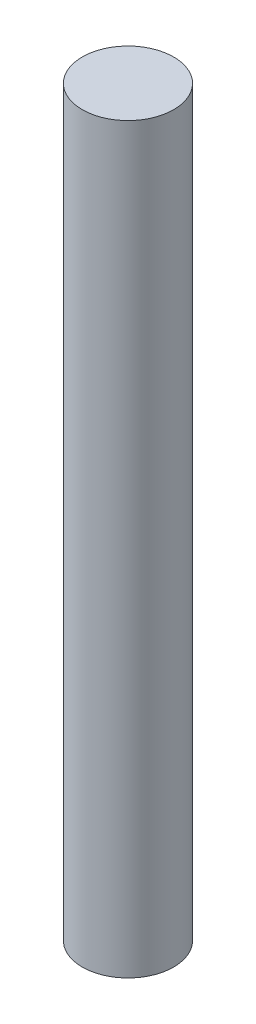
SolidWorks part; units mm, degrees
ref_plane "Front Plane" through (0, 0, 0) normal (0, 0, 1) x (1, 0, 0)
ref_plane "Top Plane" through (0, 0, 0) normal (0, 1, 0) x (1, 0, 0)
ref_plane "Right Plane" through (0, 0, 0) normal (1, 0, 0) x (0, 0, -1)
sketch "Sketch1" plane through (0, 0, 0) normal (0, 1, 0) x (1, 0, 0)
  circle A0 centre (-9.6049, -10.2521) radius 2
extrude "Boss-Extrude1" add sketch "Sketch1" along normal blind 32.5
